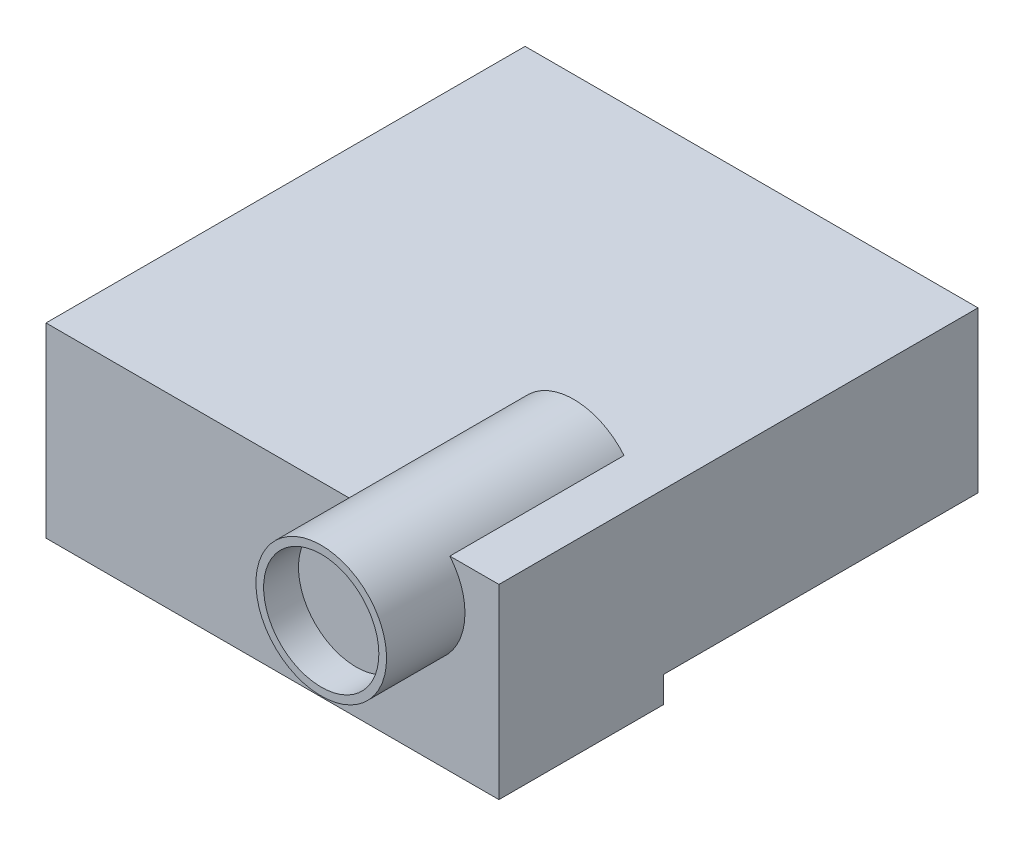
SolidWorks part; units mm, degrees
ref_plane "정면" through (0, 0, 0) normal (0, 0, 1) x (1, 0, 0)
ref_plane "윗면" through (0, 0, 0) normal (0, 1, 0) x (1, 0, 0)
ref_plane "우측면" through (0, 0, 0) normal (1, 0, 0) x (0, 0, -1)
sketch "스케치1" plane through (0, 0, 0) normal (0, 1, 0) x (1, 0, 0)
  line L1 (0, 0) -> (260, 0)
  line L2 (0, 0) -> (0, 275)
  line L3 (0, 275) -> (260, 275)
  line L4 (260, 0) -> (260, 275)
  dimension "D1" = 260
  dimension "D2" = 275
extrude "보스-돌출1" add sketch "스케치1" along normal blind 107
sketch "스케치2" plane through (0, 0, 0) normal (0, 0, 1) x (1, 0, 0)
  line L0 (260, 107) -> (260, 0) construction
  line L2 (0, 0) -> (260, 0) construction
  circle A0 centre (203, 83) radius 37.5
  dimension "D2" = 75
  dimension "D1" = 57
  dimension "D3" = 83
extrude "보스-돌출2" add sketch "스케치2" along normal blind 25 and the other way blind 100
sketch "스케치3" plane through (260, 0, 0) normal (1, 0, 0) x (0, 0, -1)
  line L0 (275, 107) -> (275, 0) construction
  line L1 (275, 15) -> (94.4841, 15)
  line L2 (275, 15) -> (275, 0)
  line L3 (275, 0) -> (94.4841, 0)
  line L4 (94.4841, 15) -> (94.4841, 0)
  line L5 (0, 0) -> (275, 0) construction
  dimension "D1" = 15
extrude "컷-돌출1" cut sketch "스케치3" against normal through all
hole_wizard "M4x0.7 나사 구멍1" positions "스케치5" profile "스케치4" tap size "M4x0.7" standard "Ansi Metric"
sketch "스케치5" plane through (0, 15, 0) normal (0, -1, 0) x (-1, 0, 0)
  line L0 (0, 235) -> (-36, 235) construction
  line L1 (0, 275) -> (0, 94.4841) construction
  line L2 (-36, 235) -> (-209, 235) construction
  line L3 (-209, 235) -> (-260, 235) construction
  line L4 (-260, 275) -> (-260, 94.4841) construction
  line L6 (0, 275) -> (-260, 275) construction
  point P0 (-36, 235)
  point P2 (-209, 235)
  dimension "D1" = 173
  dimension "D2" = 40
  dimension "D3" = 36
sketch "스케치4" plane through (36, 15, -235) normal (1, 0, 0) x (0, 0, -1)
  line L0 (0, 0) -> (0, 12.4914)
  line L1 (0, 12.4914) -> (1.65, 11.5)
  line L2 (1.65, 11.5) -> (1.65, 0)
  line L5 (1.65, 0) -> (0, 0)
  line L10 (0, 12.4914) -> (-1.65, 11.5) construction
  line L11 (0, -6.35) -> (0, 107.95) construction
  dimension "탭 드릴 지름" = 3.3
  dimension "탭 드릴 깊이" = 11.5
  dimension "드릴 각도" = 118
cosmetic thread "구멍 나사산1" parameters "D1"=8, "D2"=4
cosmetic thread "구멍 나사산2" parameters "D1"=8, "D2"=4
hole_wizard "M4x0.7 나사 구멍2" positions "스케치7" profile "스케치6" tap size "M4x0.7" standard "Ansi Metric"
sketch "스케치7" plane through (0, 0, 0) normal (0, -1, 0) x (-1, 0, 0)
  point P0 (-142, 47)
  dimension "D1" = 188
  dimension "D2" = 67
sketch "스케치6" plane through (142, 0, -47) normal (1, 0, 0) x (0, 0, -1)
  line L0 (0, 0) -> (0, 12.4914)
  line L1 (0, 12.4914) -> (1.65, 11.5)
  line L2 (1.65, 11.5) -> (1.65, 0)
  line L5 (1.65, 0) -> (0, 0)
  line L10 (0, 12.4914) -> (-1.65, 11.5) construction
  line L11 (0, -6.35) -> (0, 107.95) construction
  dimension "탭 드릴 지름" = 3.3
  dimension "탭 드릴 깊이" = 11.5
  dimension "드릴 각도" = 118
cosmetic thread "구멍 나사산3" parameters "D1"=8, "D2"=4
ref_plane "평면1" through (203, 0, 0) normal (1, 0, 0) x (0, 0, -1)
sketch "스케치17" plane through (0, 0, 25) normal (0, 0, 1) x (1, 0, 0)
  circle A0 centre (203, 83) radius 37.5
  circle A1 centre (203, 83) radius 33.0674
extrude "보스-돌출4" add sketch "스케치17" along normal blind 20
ref_plane "평면6" through (0, 0, 345) normal (0, 0, 1) x (1, 0, 0)
sketch "스케치21" plane through (203, 0, 0) normal (1, 0, 0) x (0, 0, -1)
  line L0 (-25, 83) -> (-345, 110)
  line L1 (-25, 116.0674) -> (-25, 49.9326) construction
  line L2 (-345, 294.8553) -> (-345, -294.8553) construction
  line L3 (-345, 110) -> (-345, 250)
  line L4 (-345, 250) -> (-25, 83)
  line L5 (94.4841, 0) -> (0, 0) construction
  line L6 (-125, 135.1875) -> (-125, 91.4375) construction
  line L7 (-110.6263, 127.6862) -> (-125, 113.3125) construction
  line L8 (-125, 113.3125) -> (-145.1729, 93.1396) construction
  line L10 (100, 107) -> (0, 107) construction
  line L11 (11.6875, -106.6875) -> (-155.3125, 213.3125)
  line L12 (-128.3125, -106.6875) -> (11.6875, -106.6875)
  line L13 (-155.3125, 213.3125) -> (-128.3125, -106.6875)
  dimension "D1" = 110
  dimension "D2" = 140
  dimension "D3" = 100
  dimension "D4" = 45
sketch "스케치22" plane through (0, 0, 345) normal (0, 0, 1) x (1, 0, 0)
  line L1 (295.5, 110) -> (110.5, 110)
  line L2 (295.5, 110) -> (295.5, 250)
  line L3 (295.5, 250) -> (110.5, 250)
  line L4 (110.5, 110) -> (110.5, 250)
  line L5 (295.5, 110) -> (110.5, 250) construction
  line L6 (295.5, 250) -> (110.5, 110) construction
  point P0 (203, 180)
  point P5 (203, 250)
  dimension "D1" = 185
  dimension "D2" = 140
sketch3d "3D스케치2"
  line L0 (203, 83, 25) -> (295.5, 250, 345)
  line L1 (295.5, 110, 345) -> (203, 83, 25)
  line L2 (110.5, 110, 345) -> (203, 83, 25)
  line L3 (110.5, 110, 345) -> (110.5, 250, 345) construction
  line L4 (203, 83, 25) -> (110.5, 250, 345)
ref_plane "평면7" through (0, 0, 12.5) normal (0, 0, 1) x (1, 0, 0)
ref_plane "평면8" through (0, 0, 112.5) normal (0, 0, 1) x (1, 0, 0)
